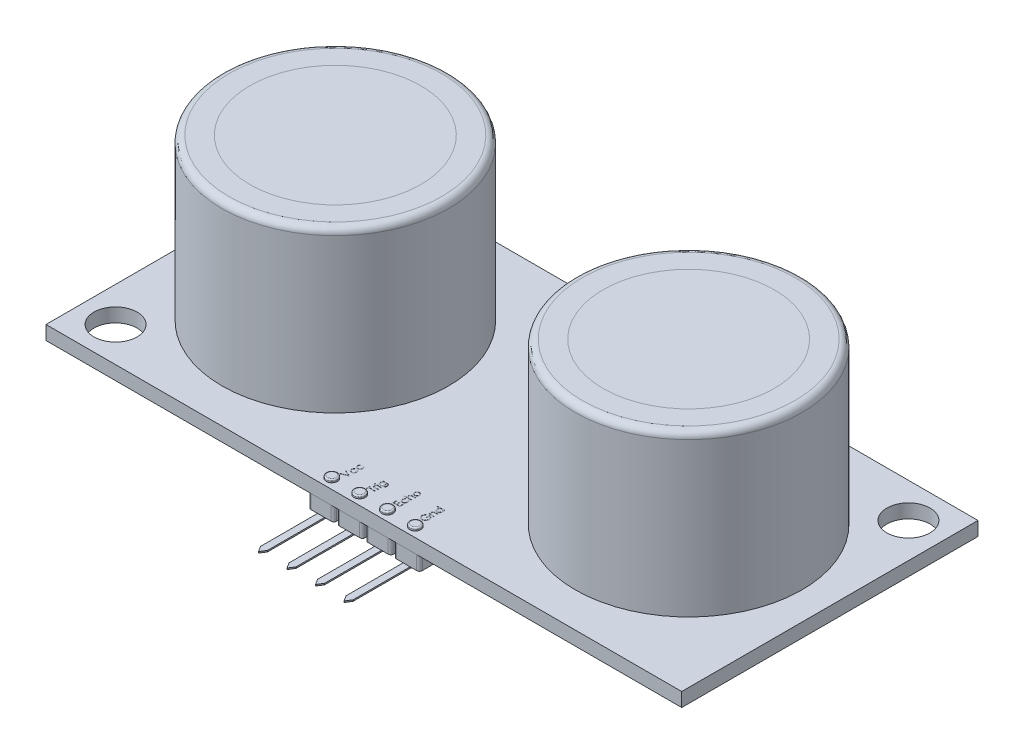
SolidWorks part; units mm, degrees
ref_plane "Front Plane" through (0, 0, 0) normal (0, 0, 1) x (1, 0, 0)
ref_plane "Top Plane" through (0, 0, 0) normal (0, 1, 0) x (1, 0, 0)
ref_plane "Right Plane" through (0, 0, 0) normal (1, 0, 0) x (0, 0, -1)
sketch "Sketch1" plane through (0, 0, 0) normal (0, 1, 0) x (1, 0, 0)
  line L1 (22.85, -10.65) -> (-22.85, -10.65)
  line L2 (22.85, -10.65) -> (22.85, 10.65)
  line L3 (22.85, 10.65) -> (-22.85, 10.65)
  line L4 (-22.85, -10.65) -> (-22.85, 10.65)
  line L5 (22.85, -10.65) -> (-22.85, 10.65) construction
  line L6 (22.85, 10.65) -> (-22.85, -10.65) construction
  circle A0 centre (20.35, 8.15) radius 1.55
  circle A1 centre (-20.35, -8.15) radius 1.55
  point P0 (0, 0)
  dimension "D3" = 3.1
  dimension "D1" = 45.7
  dimension "D2" = 21.3
  dimension "D4" = 2.5
  dimension "D5" = 2.5
  dimension "D6" = 2.5
  dimension "D7" = 2.5
extrude "Boss-Extrude1" add sketch "Sketch1" along normal blind 1
sketch "Sketch2" plane through (0, 1, 0) normal (0, 1, 0) x (1, 0, 0)
  line L0 (0, 0) -> (0, -50000) construction
  circle A0 centre (-12.7, 0) radius 8.15
  circle A1 centre (12.7, 0) radius 8.15
  circle A2 centre (-12.7, 0) radius 6.15
  circle A3 centre (12.7, 0) radius 6.15
  point P4 (20.85, 0)
  point P6 (-20.85, 0)
  dimension "D1" = 16.3
  dimension "D2" = 41.7
  dimension "D3" = 20.85
  dimension "D4" = 2
extrude "Boss-Extrude2" add sketch "Sketch2" along normal blind 11.54 separate body
fillet "Fillet1" radius 0.5 1 edges at (-12.7, 12.54, 8.15)
fillet "Fillet2" radius 0.5 1 edges at (12.7, 12.54, 8.15)
sketch "Sketch3" plane through (0, 1, 0) normal (0, 1, 0) x (1, 0, 0)
  circle A0 centre (-12.7, 0) radius 6
  circle A1 centre (12.7, 0) radius 6
  dimension "D1" = 12
extrude "Boss-Extrude3" add sketch "Sketch3" along normal blind 7 separate body
ref_plane "Plane1" through (12.7, 0, 0) normal (1, 0, 0) x (0, 0, -1)
sketch "Sketch5" plane through (12.7, 0, 0) normal (1, 0, 0) x (0, 0, -1)
  line L0 (0, 8) -> (0, -49992) construction
  line L1 (6, 8) -> (-6, 8) construction
  line L2 (0.75, 8.5) -> (0.75, 8.4)
  line L4 (0.75, 8.5) -> (0, 8.5)
  line L5 (4, 8.915) -> (2, 8)
  line L6 (0.75, 8.4) -> (0.95, 8.4)
  line L7 (0, 8.5) -> (0, 8)
  line L8 (0, 8) -> (2, 8)
  line L9 (0.95, 8.4) -> (4, 8.915)
  point P4 (0, 8)
  dimension "D1" = 4
  dimension "D2" = 0.5
  dimension "D3" = 0.75
  dimension "D4" = 0.1
  dimension "D5" = 2
  dimension "D6" = 15
  dimension "D7" = 0.2
revolve "Revolve1" add sketch "Sketch5" angle 360 about L0
pattern_linear "LPattern2" count 2 spacing 25.4 along (-1, 0, 0) of "Revolve1"
sketch "Sketch6" plane through (0, 12.54, 0) normal (0, 1, 0) x (1, 0, 0)
  circle A0 centre (-12.7, 0) radius 6.15
  circle A1 centre (12.7, 0) radius 6.15
  dimension "D1" = 12.3
extrude "Boss-Extrude4" add sketch "Sketch6" against normal blind 0.2 separate body
sketch "Sketch18" plane through (0, 0, 0) normal (0, -1, 0) x (1, 0, 0)
  line L0 (-22.85, 10.65) -> (22.85, 10.65) construction
  line L1 (-3.8, 10.65) -> (-2.35, 10.65)
  line L2 (-4, 10.45) -> (-4, 8.85)
  line L3 (-3.8, 8.65) -> (-2.35, 8.65)
  line L4 (4, 10.45) -> (4, 8.85)
  line L5 (0, 8.65) -> (0, 10.65) construction
  line L6 (-4, 9.65) -> (4, 9.65) construction
  line L7 (0, 0) -> (0, 50000) construction
  line L8 (-2.15, 10.45) -> (-2.15, 8.85)
  line L9 (0.1, 10.45) -> (0.1, 8.85)
  line L10 (-1.95, 10.45) -> (-1.95, 8.85)
  line L11 (-1.75, 10.65) -> (-0.3, 10.65)
  line L12 (-1.75, 8.65) -> (-0.3, 8.65)
  line L13 (-0.1, 8.85) -> (-0.1, 10.45)
  line L14 (0.3, 10.65) -> (1.75, 10.65)
  line L15 (0.3, 8.65) -> (1.75, 8.65)
  line L16 (1.95, 10.45) -> (1.95, 8.85)
  line L17 (2.15, 10.45) -> (2.15, 8.85)
  line L18 (2.35, 10.65) -> (3.8, 10.65)
  line L19 (2.35, 8.65) -> (3.8, 8.65)
  arc A0 (3.8, 8.65) -> (4, 8.85) centre (3.8, 8.85) ccw
  arc A1 (4, 10.45) -> (3.8, 10.65) centre (3.8, 10.45) ccw
  arc A2 (2.15, 8.85) -> (2.35, 8.65) centre (2.35, 8.85) ccw
  arc A3 (2.15, 10.45) -> (2.35, 10.65) centre (2.35, 10.45) cw
  arc A4 (1.95, 8.85) -> (1.75, 8.65) centre (1.75, 8.85) cw
  arc A5 (1.95, 10.45) -> (1.75, 10.65) centre (1.75, 10.45) ccw
  arc A6 (0.1, 8.85) -> (0.3, 8.65) centre (0.3, 8.85) ccw
  arc A7 (0.1, 10.45) -> (0.3, 10.65) centre (0.3, 10.45) cw
  arc A8 (-0.1, 8.85) -> (-0.3, 8.65) centre (-0.3, 8.85) cw
  arc A9 (-0.1, 10.45) -> (-0.3, 10.65) centre (-0.3, 10.45) ccw
  arc A10 (-1.95, 10.45) -> (-1.75, 10.65) centre (-1.75, 10.45) cw
  arc A11 (-1.95, 8.85) -> (-1.75, 8.65) centre (-1.75, 8.85) ccw
  arc A12 (-2.35, 8.65) -> (-2.15, 8.85) centre (-2.35, 8.85) ccw
  arc A13 (-2.15, 10.45) -> (-2.35, 10.65) centre (-2.35, 10.45) ccw
  arc A14 (-4, 8.85) -> (-3.8, 8.65) centre (-3.8, 8.85) ccw
  arc A15 (-4, 10.45) -> (-3.8, 10.65) centre (-3.8, 10.45) cw
  point P24 (4, 10.65)
  point P27 (2.15, 8.65)
  point P30 (2.15, 10.65)
  point P33 (1.95, 8.65)
  point P38 (0.1, 8.65)
  point P41 (0.1, 10.65)
  point P46 (-0.1, 10.65)
  point P49 (-1.95, 10.65)
  point P52 (-1.95, 8.65)
  point P59 (-4, 8.65)
  point P62 (-4, 10.65)
  point P212 (0, 9.65)
extrude "Boss-Extrude10" add sketch "Sketch18" along normal blind 1 separate body
sketch "Sketch13" plane through (0, 1, 0) normal (0, 1, 0) x (1, 0, 0)
  line L0 (-4, -10.65) -> (-4, -8.7338) construction
  line L1 (-22.85, -10.65) -> (22.85, -10.65) construction
  line L2 (-4, -8.7338) -> (4, -8.7338) construction
  line L3 (4, -8.7338) -> (4, -10.65) construction
  line L4 (4, -10.65) -> (-4, -10.65) construction
  line L5 (0, 0) -> (0, -50000) construction
  circle A0 centre (-3, -9.95) radius 0.4
  circle A1 centre (-1, -9.95) radius 0.4
  circle A2 centre (1, -9.95) radius 0.4
  circle A3 centre (3, -9.95) radius 0.4
  point P9 (-4, -9.6919)
extrude "Boss-Extrude8" add sketch "Sketch13" along normal blind 0.2 separate body
fillet "Fillet3" radius 0.1 1 edges at (-3, 1.2, 10.35)
fillet "Fillet4" radius 0.1 1 edges at (-1, 1.2, 10.35)
fillet "Fillet5" radius 0.1 1 edges at (1, 1.2, 10.35)
fillet "Fillet6" radius 0.1 1 edges at (3, 1.2, 10.35)
sketch "Sketch15" plane through (0, 1, 0) normal (0, 1, 0) x (1, 0, 0)
  line L0 (-22.85, -10.65) -> (22.85, -10.65) construction
  line L1 (3.4865, -7.65) -> (-2.4849, -7.65) construction
  line L2 (3.4865, -7.65) -> (3.4865, -10.65) construction
  line L3 (3.4865, -10.65) -> (-2.4849, -10.65) construction
  line L5 (-2.4849, -7.65) -> (-2.4849, -10.65) construction
  line L6 (3.4865, -7.65) -> (-2.4849, -10.65) construction
  line L7 (3.4865, -10.65) -> (-2.4849, -7.65) construction
  text T0 "Vcc  \r\nTrig   \r\nEcho\r\nGnd " font "Century Gothic" height 0.5
  point P0 (0.5008, -9.15)
  dimension "D1" = 3
extrude "Cut-Extrude5" cut sketch "Sketch15" against normal blind 0.01
sketch "Sketch19" plane through (0, -1, 0) normal (0, -1, 0) x (1, 0, 0)
  line L1 (3.325, 9.15) -> (2.825, 9.15)
  line L2 (3.325, 9.15) -> (3.325, 14.75)
  line L3 (3.075, 15.15) -> (2.825, 15.15)
  line L4 (2.825, 9.15) -> (2.825, 14.75)
  line L5 (3.075, 15.15) -> (3.075, 9.15) construction
  line L6 (3.325, 12.15) -> (2.825, 12.15) construction
  line L7 (1.275, 9.15) -> (0.775, 9.15)
  line L8 (1.275, 9.15) -> (1.275, 14.75)
  line L9 (1.025, 15.15) -> (0.775, 15.15)
  line L10 (0.775, 9.15) -> (0.775, 14.75)
  line L11 (1.025, 15.15) -> (1.025, 9.15) construction
  line L12 (1.275, 12.15) -> (0.775, 12.15) construction
  line L13 (-0.775, 9.15) -> (-1.275, 9.15)
  line L14 (-0.775, 9.15) -> (-0.775, 14.75)
  line L15 (-1.025, 15.15) -> (-1.275, 15.15)
  line L16 (-1.275, 9.15) -> (-1.275, 14.75)
  line L17 (-1.025, 15.15) -> (-1.025, 9.15) construction
  line L18 (-0.775, 12.15) -> (-1.275, 12.15) construction
  line L19 (-2.825, 9.15) -> (-3.325, 9.15)
  line L20 (-2.825, 9.15) -> (-2.825, 14.75)
  line L21 (-3.075, 15.15) -> (-3.325, 15.15)
  line L22 (-3.325, 9.15) -> (-3.325, 14.75)
  line L23 (-3.075, 15.15) -> (-3.075, 9.15) construction
  line L24 (-2.825, 12.15) -> (-3.325, 12.15) construction
  line L26 (-1.75, 8.65) -> (-0.3, 8.65) construction
  line L27 (-3.8, 8.65) -> (-2.35, 8.65) construction
  line L29 (-3.075, 15.15) -> (-2.825, 14.75)
  line L30 (-3.075, 15.15) -> (-3.325, 14.75)
  line L31 (-1.025, 15.15) -> (-0.775, 14.75)
  line L32 (1.025, 15.15) -> (1.275, 14.75)
  line L33 (-1.275, 14.75) -> (-1.025, 15.15)
  line L34 (1.025, 15.15) -> (0.775, 14.75)
  line L35 (3.075, 15.15) -> (3.325, 14.75)
  line L37 (2.825, 14.75) -> (3.075, 15.15)
  point P20 (-1.025, 8.65)
  point P23 (-3.075, 8.65)
  point P300 (-1.025, 12.15)
  point P301 (-3.075, 12.15)
  point P352 (1.025, 12.15)
  point P420 (3.075, 12.15)
  dimension "D2" = 6
  dimension "D3" = 0.5
  dimension "D4" = 0.5
  dimension "D5" = 0.5
  dimension "D6" = 0.5
  dimension "D7" = 0.4
  dimension "D8" = 0.4
  dimension "D9" = 0.4717
extrude "Boss-Extrude11" add sketch "Sketch19" along normal blind 0.1 separate body contours L29 L20 L19 L22 L30 | L31 L14 L13 L16 L33 | L32 L8 L7 L10 L34 | L35 L2 L1 L4 L37
sketch "Sketch21" plane through (0, 1, 0) normal (0, 1, 0) x (1, 0, 0)
  line L0 (22.85, 10.65) -> (-22.85, 10.65) construction
  line L1 (3, 6.65) -> (-3, 6.65)
  line L3 (3, 9.65) -> (-3, 9.65)
  arc A0 (-3, 9.65) -> (-3, 6.65) centre (-3, 8.15) ccw
  arc A1 (3, 6.65) -> (3, 9.65) centre (3, 8.15) ccw
  point P14 (-4.5, 8.15)
  point P16 (4.5, 8.15)
  dimension "D1" = 3
  dimension "D2" = 6
  dimension "D3" = 1
extrude "Boss-Extrude13" add sketch "Sketch21" along normal blind 0.5 separate body
sketch "Sketch22" plane through (0, 1.5, 0) normal (0, 1, 0) x (1, 0, 0)
  line L1 (-2.9874, 7.15) -> (3, 7.15)
  line L3 (-3, 9.15) -> (3, 9.15)
  line L4 (-3, 6.65) -> (3, 6.65) construction
  arc A0 (-3, 9.15) -> (-2.9874, 7.15) centre (-3, 8.15) ccw
  arc A1 (3, 7.15) -> (3, 9.15) centre (3, 8.15) ccw
  arc A2 (-3, 9.65) -> (-3, 6.65) centre (-3, 8.15) ccw construction
  arc A3 (3, 6.65) -> (3, 9.65) centre (3, 8.15) ccw construction
  point P2 (4.5, 8.15)
  point P3 (4, 8.15)
  point P4 (-4.5, 8.15)
  point P5 (-4, 8.1437)
  dimension "D1" = 0.5
  dimension "D3" = 1
  dimension "D2" = 2
  dimension "D4" = 0.5
  dimension "D5" = 0.5
extrude "Boss-Extrude14" add sketch "Sketch22" along normal blind 1.5
fillet "Fillet7" radius 0.1 8 edges at (-4, 3, -8.1437) (0, 3, -9.15) (4, 3, -8.15) (-4.5, 1.5, -8.15) (0, 1.5, -9.65) (4.5, 1.5, -8.15) (0.0063, 3, -7.15) (0, 1.5, -6.65)
sketch "Sketch23" plane through (0, 12.54, 0) normal (0, 1, 0) x (1, 0, 0)
  circle A0 centre (-12.7, 0) radius 6.15 construction
equation "\"D2@Sketch13\"=\"D1@Sketch13\"/2"
equation "\"D9@Sketch18\"=\"D1@Sketch18\"/2"
